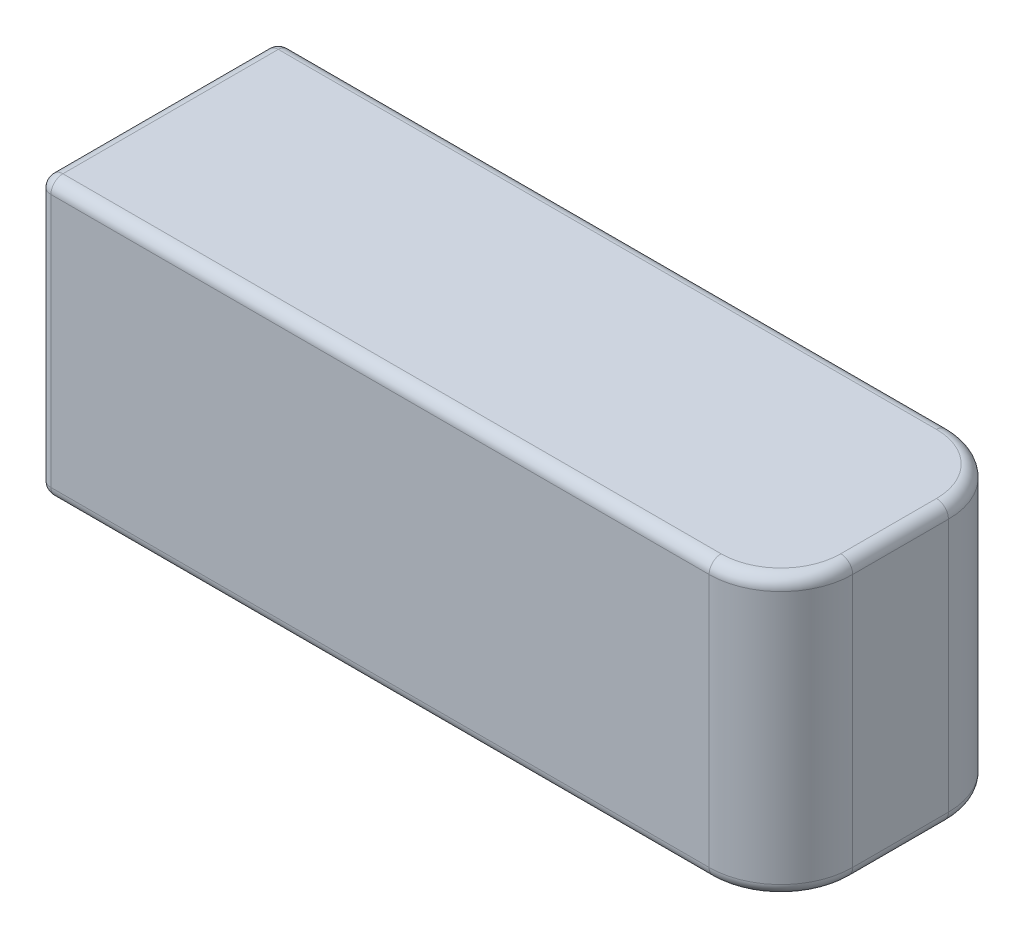
SolidWorks part; units mm, degrees
ref_plane "Front Plane" through (0, 0, 0) normal (0, 0, 1) x (1, 0, 0)
ref_plane "Top Plane" through (0, 0, 0) normal (0, 1, 0) x (1, 0, 0)
ref_plane "Right Plane" through (0, 0, 0) normal (1, 0, 0) x (0, 0, -1)
sketch "Sketch1" plane through (0, 0, 0) normal (0, 1, 0) x (1, 0, 0)
  line L1 (-77.5, 25) -> (77.5, 25)
  line L2 (-77.5, 25) -> (-77.5, -25)
  line L3 (-77.5, -25) -> (77.5, -25)
  line L4 (77.5, 25) -> (77.5, -25)
  point P4 (77.5, 0)
  point P5 (0, 25)
  dimension "D1" = 155
  dimension "D2" = 50
extrude "Boss-Extrude1" add sketch "Sketch1" along normal blind 58
fillet "Fillet1" radius 15 2 edges at (77.5, 29, -25) (77.5, 29, 25)
fillet "Fillet2" radius 2.5 14 edges at (73.1066, 58, 20.6066) (-77.5, 58, 0) (-7.5, 58, -25) (73.1066, 58, -20.6066) (77.5, 58, 0) (-77.5, 0, 0) (73.1066, 0, 20.6066) (77.5, 0, 0) (73.1066, 0, -20.6066) (-7.5, 0, -25) (-77.5, 29, 25) (-7.5, 58, 25) (-7.5, 0, 25) (-77.5, 29, -25)
